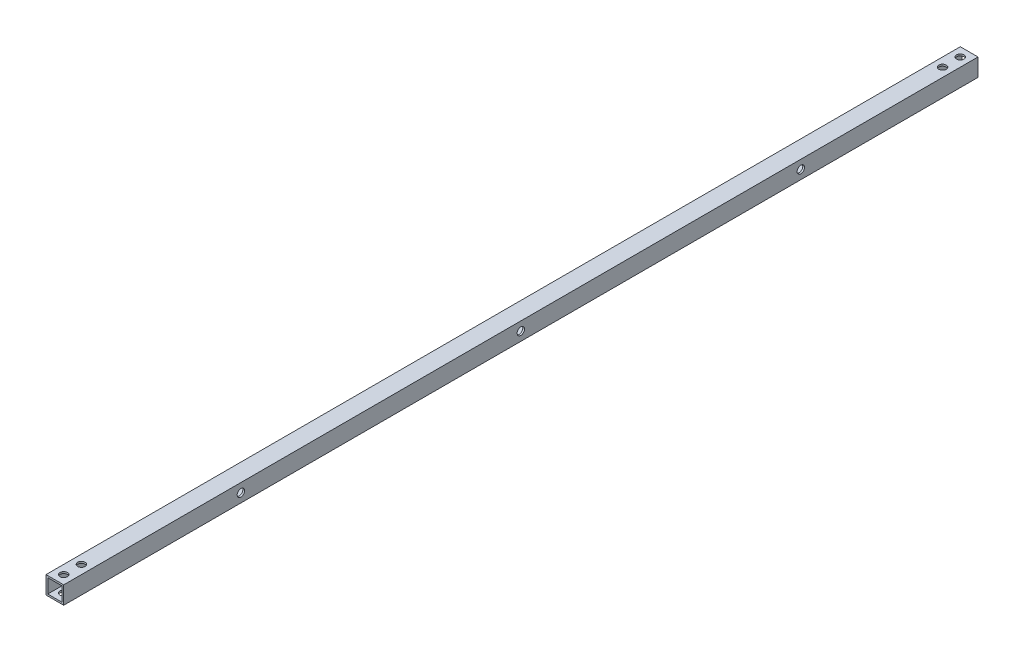
SolidWorks part; units mm, degrees
ref_plane "Front Plane" through (0, 0, 0) normal (0, 0, 1) x (1, 0, 0)
ref_plane "Top Plane" through (0, 0, 0) normal (0, 1, 0) x (1, 0, 0)
ref_plane "Right Plane" through (0, 0, 0) normal (1, 0, 0) x (0, 0, -1)
sketch "Sketch1" plane through (0, 0, 0) normal (0, 0, 1) x (1, 0, 0)
  line L0 (0, 0) -> (10, 0)
  line L1 (0, 0) -> (0, 10)
  line L2 (0, 10) -> (10, 10)
  line L3 (10, 0) -> (10, 10)
  line L4 (1, 9) -> (9, 9)
  line L5 (1, 9) -> (1, 1)
  line L6 (1, 1) -> (9, 1)
  line L7 (9, 9) -> (9, 1)
  dimension "D1" = 10
  dimension "D2" = 10
  dimension "D3" = 8
  dimension "D4" = 8
  dimension "D5" = 1
  dimension "D6" = 1
  dimension "D7" = 0
extrude "Boss-Extrude1" add sketch "Sketch1" along normal blind 516
sketch "Sketch2" plane through (0, 10, 0) normal (0, 1, 0) x (1, 0, 0)
  line L0 (10, -516) -> (10, 0) construction
  line L1 (10, 0) -> (0, 0) construction
  line L2 (10, -516) -> (0, -516) construction
  circle A0 centre (5, -5) radius 2.1
  circle A1 centre (5, -15) radius 2.1
  circle A2 centre (5, -501) radius 2.1
  circle A3 centre (5, -511) radius 2.1
  dimension "D1" = 4.2
  dimension "D2" = 4.2
  dimension "D7" = 4.2
  dimension "D8" = 4.2
  dimension "D3" = 5
  dimension "D4" = 5
  dimension "D5" = 5
  dimension "D6" = 15
  dimension "D9" = 5
  dimension "D10" = 5
  dimension "D11" = 5
  dimension "D12" = 15
extrude "Cut-Extrude1" cut sketch "Sketch2" against normal blind 116
sketch "Sketch3" plane through (0, 0, 0) normal (0, -1, 0) x (1, 0, 0)
  line L0 (10, 516) -> (10, 0) construction
  line L1 (0, 516) -> (10, 516) construction
  line L2 (0, 0) -> (10, 0) construction
  circle A0 centre (5, 308) radius 2.1
  circle A1 centre (5, 208) radius 2.1
  dimension "D1" = 4.2
  dimension "D2" = 5
  dimension "D3" = 208
  dimension "D4" = 4.2
  dimension "D5" = 5
  dimension "D6" = 208
extrude "Cut-Extrude2" cut sketch "Sketch3" against normal blind 5
sketch "Sketch4" plane through (10, 0, 0) normal (1, 0, 0) x (0, 0, -1)
  line L0 (0, 0) -> (0, 10) construction
  line L1 (-516, 0) -> (-516, 10) construction
  line L2 (-516, 0) -> (0, 0) construction
  circle A0 centre (-416, 5) radius 2.1
  circle A1 centre (-100, 5) radius 2.1
  circle A2 centre (-258, 5) radius 2.1
  dimension "D1" = 4.2
  dimension "D2" = 4.2
  dimension "D5" = 4.2
  dimension "D3" = 100
  dimension "D4" = 100
  dimension "D6" = 258
  dimension "D7" = 5
extrude "Cut-Extrude3" cut sketch "Sketch4" against normal blind 10
